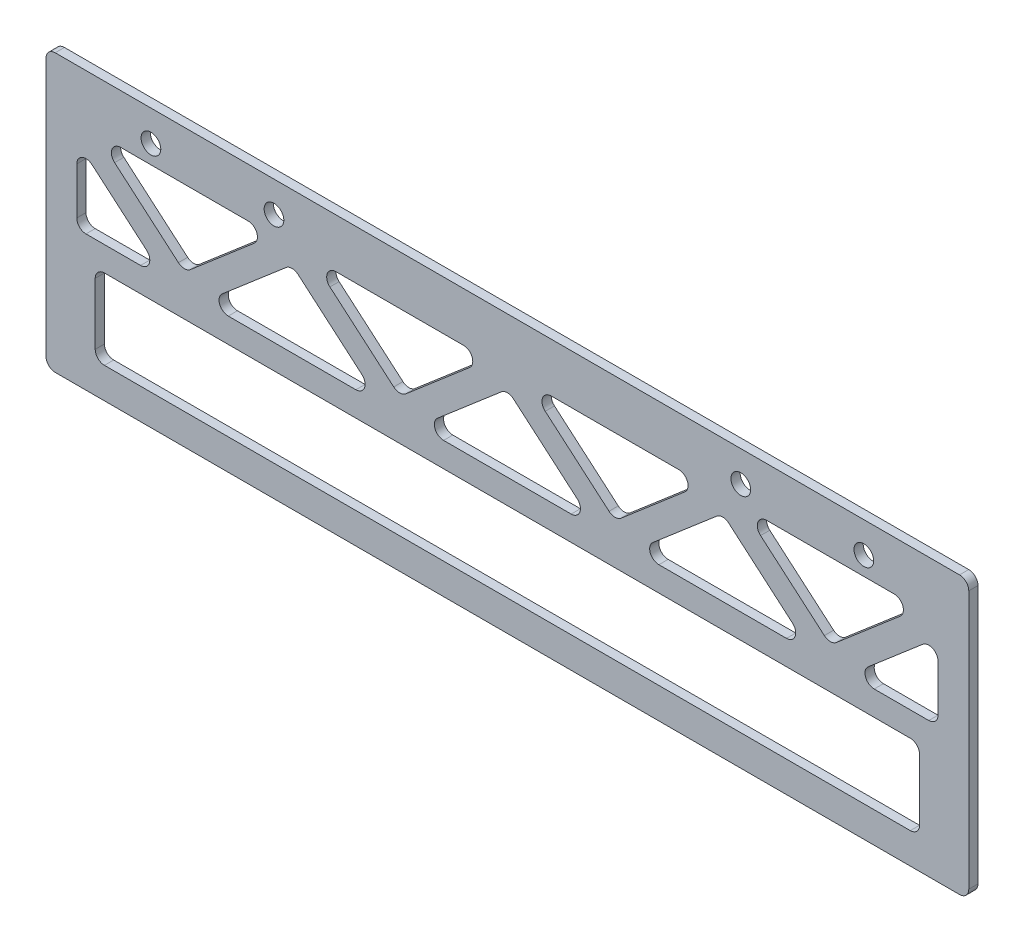
SolidWorks part; units mm, degrees
material "Thornel Mat VMA"
ref_plane "前视基准面" through (0, 0, 0) normal (0, 0, 1) x (1, 0, 0)
ref_plane "上视基准面" through (0, 0, 0) normal (0, 1, 0) x (1, 0, 0)
ref_plane "右视基准面" through (0, 0, 0) normal (1, 0, 0) x (0, 0, -1)
sketch "草图1" plane through (0, 0, 0) normal (0, 0, 1) x (1, 0, 0)
  line L1 (-75, 22.5) -> (75, 22.5)
  line L2 (-75, 22.5) -> (-75, -22.5)
  line L3 (-75, -22.5) -> (75, -22.5)
  line L4 (75, 22.5) -> (75, -22.5)
  line L5 (-75, 22.5) -> (75, -22.5) construction
  line L6 (-75, -22.5) -> (75, 22.5) construction
  point P0 (0, 0)
  dimension "D1" = 150
  dimension "D2" = 45
extrude "凸台-拉伸1" add sketch "草图1" along normal blind 1.5
sketch "草图2" plane through (0, 0, 1.5) normal (0, 0, 1) x (1, 0, 0)
  line L0 (-75, -22.5) -> (75, -22.5) construction
  line L1 (-67, -4.5) -> (67, -4.5)
  line L2 (-67, -4.5) -> (-67, -17.5)
  line L3 (-67, -17.5) -> (67, -17.5)
  line L4 (67, -4.5) -> (67, -17.5)
  line L5 (-67, -4.5) -> (67, -17.5) construction
  line L6 (-67, -17.5) -> (67, -4.5) construction
  line L7 (75, -22.5) -> (75, 22.5) construction
  line L8 (-75, 22.5) -> (-75, -22.5) construction
  circle A0 centre (37.9423, 17.5) radius 1.5 construction
  circle A1 centre (57.9423, 17.5) radius 1.5 construction
  circle A2 centre (-37.9423, 17.5) radius 1.5 construction
  circle A3 centre (-57.9423, 17.5) radius 1.5 construction
  circle A4 centre (37.9423, 17.5) radius 1.5 construction
  circle A5 centre (57.9423, 17.5) radius 1.5 construction
  circle A6 centre (-37.9423, 17.5) radius 1.5 construction
  circle A7 centre (-57.9423, 17.5) radius 1.5 construction
  circle A8 centre (37.9423, 17.5) radius 1.6
  circle A9 centre (57.9423, 17.5) radius 1.6
  circle A10 centre (-37.9423, 17.5) radius 1.6
  circle A11 centre (-57.9423, 17.5) radius 1.6
  point P0 (0, -11)
  dimension "D5" = 0.1
  dimension "D1" = 5
  dimension "D2" = 8
  dimension "D3" = 8
  dimension "D4" = 13
extrude "切除-拉伸1" cut sketch "草图2" against normal through all
sketch "草图3" plane through (0, 0, 1.5) normal (0, 0, 1) x (1, 0, 0)
  line L0 (75, 22.5) -> (-75, 22.5) construction
  line L1 (-70, 14.5) -> (70, 14.5)
  line L2 (-70, 14.5) -> (-70, -0.5)
  line L3 (-70, -0.5) -> (70, -0.5)
  line L4 (70, 14.5) -> (70, -0.5)
  line L5 (-70, 14.5) -> (70, -0.5) construction
  line L6 (-70, -0.5) -> (70, 14.5) construction
  line L7 (75, -22.5) -> (75, 22.5) construction
  line L8 (-70, 14.5) -> (-52.5, -0.5)
  line L9 (-52.5, -0.5) -> (-35, 14.5)
  line L10 (-35, 14.5) -> (-17.5, -0.5)
  line L11 (-17.5, -0.5) -> (0, 14.5)
  line L12 (0, 14.5) -> (17.5, -0.5)
  line L13 (17.5, -0.5) -> (35, 14.5)
  line L14 (35, 14.5) -> (52.5, -0.5)
  line L15 (52.5, -0.5) -> (70, 14.5)
  line L16 (-71.3016, 12.9815) -> (-52.5, -3.1342)
  line L17 (-52.5, -3.1342) -> (-35, 11.8658)
  line L18 (-35, 11.8658) -> (-17.5, -3.1342)
  line L19 (-17.5, -3.1342) -> (0, 11.8658)
  line L20 (0, 11.8658) -> (17.5, -3.1342)
  line L21 (17.5, -3.1342) -> (35, 11.8658)
  line L22 (35, 11.8658) -> (52.5, -3.1342)
  line L23 (52.5, -3.1342) -> (71.3016, 12.9815)
  line L24 (-68.6984, 16.0185) -> (-52.5, 2.1342)
  line L25 (-52.5, 2.1342) -> (-35, 17.1342)
  line L26 (-35, 17.1342) -> (-17.5, 2.1342)
  line L27 (-17.5, 2.1342) -> (0, 17.1342)
  line L28 (0, 17.1342) -> (17.5, 2.1342)
  line L29 (17.5, 2.1342) -> (35, 17.1342)
  line L30 (35, 17.1342) -> (52.5, 2.1342)
  line L31 (52.5, 2.1342) -> (68.6984, 16.0185)
  point P0 (0, 7)
  point P14 (-128.6177, 4.3658)
  dimension "D2" = 5
  dimension "D1" = 8
  dimension "D3" = 15
  dimension "D4" = 2
  dimension "D5" = 2
extrude "切除-拉伸2" cut sketch "草图3" against normal through all contours L16 L2 L3 | L24 L25 L1 | L18 L17 L3 | L26 L27 L1 | L20 L19 L3 | L28 L29 L1 | L22 L21 L3 | L30 L31 L1 | L23 L3 L4
fillet "圆角1" radius 1.5 35 edges at (-14.4268, -0.5, 0.75) (14.4268, -0.5, 0.75) (0, 11.8658, 0.75) (-49.4268, -0.5, 0.75) (-20.5732, -0.5, 0.75) (-35, 11.8658, 0.75) (70, -0.5, 0.75) (70, 11.8658, 0.75) (55.5732, -0.5, 0.75) (20.5732, -0.5, 0.75) (49.4268, -0.5, 0.75) (35, 11.8658, 0.75) (-70, -0.5, 0.75) (-55.5732, -0.5, 0.75) (-70, 11.8658, 0.75) (-75, -22.5, 0.75) (-75, 22.5, 0.75) (75, 22.5, 0.75) (67, -4.5, 0.75) (-67, -4.5, 0.75) (-67, -17.5, 0.75) (67, -17.5, 0.75) (17.5, 2.1342, 0.75) (31.9268, 14.5, 0.75) (3.0732, 14.5, 0.75) (52.5, 2.1342, 0.75) (66.9268, 14.5, 0.75) (38.0732, 14.5, 0.75) (-52.5, 2.1342, 0.75) (-38.0732, 14.5, 0.75) (-66.9268, 14.5, 0.75) (-17.5, 2.1342, 0.75) (-3.0732, 14.5, 0.75) (-31.9268, 14.5, 0.75) (75, -22.5, 0.75)
